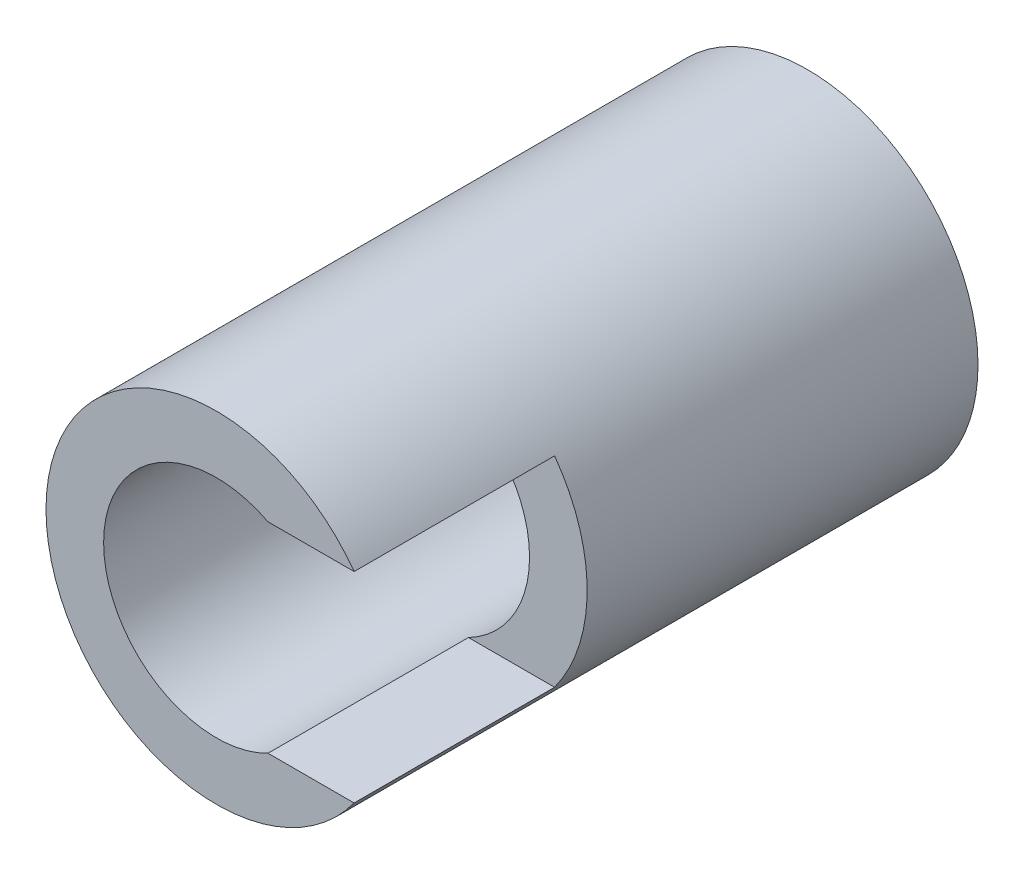
SolidWorks part; units mm, degrees
ref_plane "前视基准面" through (0, 0, 0) normal (0, 0, 1) x (1, 0, 0)
ref_plane "上视基准面" through (0, 0, 0) normal (0, 1, 0) x (1, 0, 0)
ref_plane "右视基准面" through (0, 0, 0) normal (1, 0, 0) x (0, 0, -1)
other "Configuration Table"
sketch "草图1" plane through (0, 0, 0) normal (0, 0, 1) x (1, 0, 0)
  circle A0 centre (0, 0) radius 2.25
  circle A1 centre (0, 0) radius 3.4
  dimension "D1" = 4.5
  dimension "D2" = 6.8
extrude "凸台-拉伸1" add sketch "草图1" along normal blind 11.8
sketch "草图2" plane through (0, 0, 11.8) normal (0, 0, 1) x (1, 0, 0)
  line L1 (-0.9157, -2) -> (6.1633, -2)
  line L2 (-0.9157, -2) -> (-0.9157, 2)
  line L3 (-0.9157, 2) -> (6.1633, 2)
  line L4 (6.1633, -2) -> (6.1633, 2)
  line L5 (-0.9157, -2) -> (6.1633, 2) construction
  line L6 (-0.9157, 2) -> (6.1633, -2) construction
  point P0 (2.6238, 0)
  dimension "D1" = 4
extrude "切除-拉伸1" cut sketch "草图2" against normal blind 4
